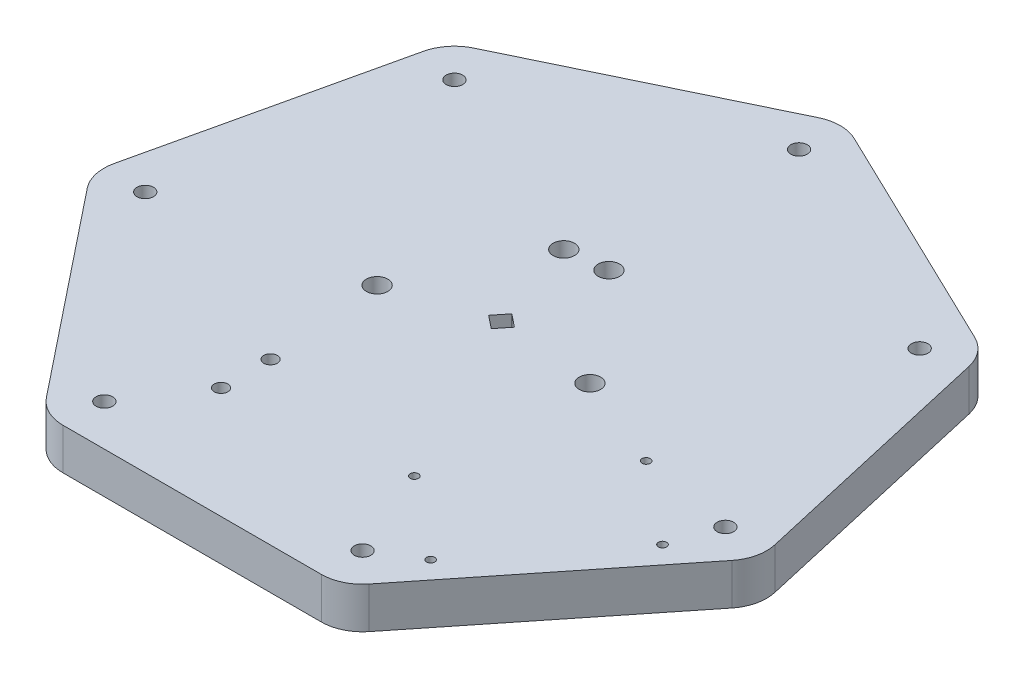
SolidWorks part; units mm, degrees
ref_plane "Front Plane" through (0, 0, 0) normal (0, 0, 1) x (1, 0, 0)
ref_plane "Top Plane" through (0, 0, 0) normal (0, 1, 0) x (1, 0, 0)
ref_plane "Right Plane" through (0, 0, 0) normal (1, 0, 0) x (0, 0, -1)
sketch "Sketch1" plane through (0, 0, 0) normal (0, 1, 0) x (1, 0, 0)
  line L0 (-20, -75) -> (-20, -36) construction
  line L1 (80.085, -13.8285) -> (66.1542, 47.2066)
  line L2 (60.7437, 53.9911) -> (4.3388, 81.1542)
  line L3 (-4.3388, 81.1542) -> (-60.7437, 53.9911)
  line L4 (-66.1542, 47.2066) -> (-80.085, -13.8285)
  line L5 (-78.1541, -22.2886) -> (-39.1207, -71.2349)
  line L6 (-31.3024, -75) -> (31.3024, -75)
  line L7 (39.1207, -71.2349) -> (78.1541, -22.2886)
  line L8 (0, 0) -> (0, -75) construction
  line L9 (0.3167, -2.8106) -> (-0.3167, 2.8106) construction
  line L10 (0.3167, -2.8106) -> (2.8106, 0.3167)
  line L11 (0.3167, -2.8106) -> (-2.8106, -0.3167)
  line L12 (-2.8106, -0.3167) -> (-0.3167, 2.8106)
  line L13 (2.8106, 0.3167) -> (-0.3167, 2.8106)
  line L14 (0, 0) -> (-56.4049, 44.9814) construction
  line L15 (-22.6336, -7.5313) -> (2.306, 23.742) construction
  line L16 (0, 0) -> (8.1054, 10.1638) construction
  line L17 (-7.5313, 22.6336) -> (23.742, -2.306) construction
  line L18 (21.9308, -43.0702) -> (41.4766, -58.6574) construction
  line L19 (41.4766, -58.6574) -> (66.4162, -27.3842) construction
  line L20 (66.4162, -27.3842) -> (46.8704, -11.7969) construction
  line L21 (53.9464, -43.0208) -> (58.6374, -46.7617) construction
  circle A0 centre (0, 0) radius 75 construction
  arc A1 (-31.3024, -75) -> (-39.1207, -71.2349) centre (-31.3024, -65) cw
  arc A2 (-78.1541, -22.2886) -> (-80.085, -13.8285) centre (-70.3357, -16.0537) cw
  arc A3 (-66.1542, 47.2066) -> (-60.7437, 53.9911) centre (-56.4049, 44.9814) cw
  arc A4 (-4.3388, 81.1542) -> (4.3388, 81.1542) centre (0, 72.1446) cw
  arc A5 (60.7437, 53.9911) -> (66.1542, 47.2066) centre (56.4049, 44.9814) cw
  arc A6 (80.085, -13.8285) -> (78.1541, -22.2886) centre (70.3357, -16.0537) cw
  arc A7 (39.1207, -71.2349) -> (31.3024, -75) centre (31.3024, -65) cw
  circle A8 centre (-31.3024, -65) radius 2
  circle A10 centre (70.3357, -16.0537) radius 2
  circle A12 centre (0, 72.1446) radius 2
  circle A13 centre (56.4049, 44.9814) radius 2
  circle A14 centre (-56.4049, 44.9814) radius 2
  circle A15 centre (-70.3357, -16.0537) radius 2
  circle A16 centre (31.3024, -65) radius 2
  circle A17 centre (-20, -48) radius 1.65
  circle A18 centre (-20, -36) radius 1.65
  circle A19 centre (-22.6336, -7.5313) radius 2.6
  circle A20 centre (2.306, 23.742) radius 2.6
  circle A21 centre (-7.5313, 22.6336) radius 2.6
  circle A22 centre (23.742, -2.306) radius 2.6
  circle A23 centre (41.4766, -58.6574) radius 1
  circle A24 centre (66.4162, -27.3842) radius 1
  circle A25 centre (46.8704, -11.7969) radius 1
  circle A26 centre (21.9308, -43.0702) radius 1
  point P34 (0, 0)
  point P44 (-10.1638, 8.1054)
  dimension "D1" = 150
  dimension "D2" = 10
  dimension "D3" = 4
  dimension "D4" = 3.3
  dimension "D11" = 5.2
  dimension "D13" = 2
  dimension "D5" = 12
  dimension "D6" = 36
  dimension "D7" = 20
  dimension "D8" = 40
  dimension "D9" = 4
  dimension "D10" = 13
  dimension "D12" = 13
  dimension "D14" = 40
  dimension "D15" = 25
  dimension "D16" = 6
extrude "Boss-Extrude1" add sketch "Sketch1" along normal blind 10
